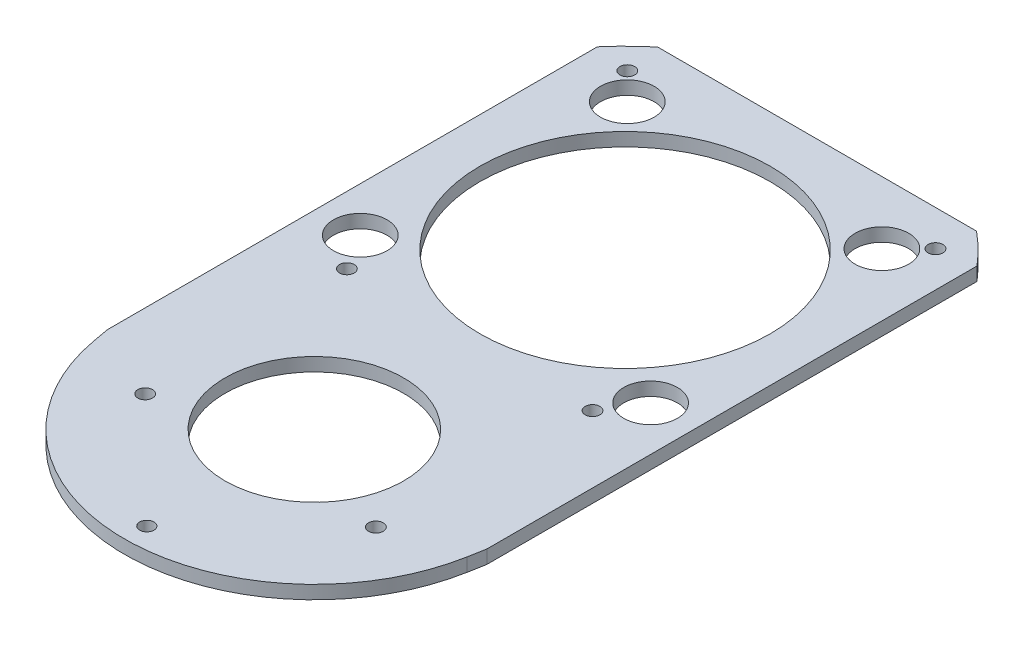
SolidWorks part; units mm, degrees
ref_plane "Front Plane" through (0, 0, 0) normal (0, 0, 1) x (1, 0, 0)
ref_plane "Top Plane" through (0, 0, 0) normal (0, 1, 0) x (1, 0, 0)
ref_plane "Right Plane" through (0, 0, 0) normal (1, 0, 0) x (0, 0, -1)
sketch "Sketch1" plane through (0, 0, 0) normal (0, 1, 0) x (1, 0, 0)
  line L0 (0, 0) -> (0, -69.5691) construction
  line L1 (0, 0) -> (0, -69.5691) construction
  line L2 (-42.5, -73.412) -> (-41.8107, -77.1925)
  line L3 (42.5, -73.412) -> (41.8107, -77.1925)
  line L4 (42.5, 36.2892) -> (42.5, -73.412)
  line L5 (-22.5, -47.0691) -> (22.5, -47.0691) construction
  line L6 (-35.6953, 43) -> (35.6953, 43)
  line L7 (-22.5, -47.0691) -> (-22.5, -92.0691) construction
  line L8 (-22.5, -92.0691) -> (22.5, -92.0691) construction
  line L9 (22.5, -47.0691) -> (22.5, -92.0691) construction
  line L10 (-22.5, -47.0691) -> (22.5, -92.0691) construction
  line L11 (-22.5, -92.0691) -> (22.5, -47.0691) construction
  line L12 (-42.5, 36.2892) -> (-42.5, -73.412)
  arc A0 (42.5, 36.2892) -> (35.6953, 43) centre (0, 0) ccw
  arc A1 (-41.8107, -77.1925) -> (41.8107, -77.1925) centre (0, -69.5691) ccw
  circle A2 centre (0, 0) radius 32.5
  circle A3 centre (0, -69.5691) radius 20
  arc A4 (-35.6953, 43) -> (-42.5, 36.2892) centre (0, 0) ccw
  point P1 (0, -34.7846)
  dimension "D1" = 65
  dimension "D2" = 40
  dimension "D7" = 85
  dimension "D3" = 69.5691
  dimension "D4" = 43
  dimension "D5" = 45
  dimension "D6" = 45
  dimension "D8" = 42.5
  dimension "D9" = 42.5
extrude "Boss-Extrude1" add sketch "Sketch1" along normal blind 3
sketch "Sketch4" plane through (0, 3, 0) normal (0, 1, 0) x (1, 0, 0)
  line L1 (-22.5, -47.0691) -> (22.5, -47.0691)
  line L2 (-22.5, -47.0691) -> (-22.5, -92.0691)
  line L3 (-22.5, -92.0691) -> (22.5, -92.0691)
  line L4 (22.5, -47.0691) -> (22.5, -92.0691)
  line L5 (-22.5, -47.0691) -> (22.5, -92.0691) construction
  line L6 (-22.5, -92.0691) -> (22.5, -47.0691) construction
  circle A0 centre (0, 0) radius 42.5
  point P3 (0, -69.5691)
  dimension "D1" = 45
  dimension "D2" = 45
sketch "Sketch5" plane through (0, 3, 0) normal (0, 1, 0) x (1, 0, 0)
  circle A0 centre (0, -107.0691) radius 1.6
  arc A1 (-41.8107, -77.1925) -> (41.8107, -77.1925) centre (0, -69.5691) ccw construction
  dimension "D2" = 3.2
  dimension "D1" = 37.5
extrude "Cut-Extrude1" cut sketch "Sketch5" against normal blind 10
sketch "Sketch6" plane through (0, 3, 0) normal (0, 1, 0) x (1, 0, 0)
  line L0 (35.6953, 43) -> (-35.6953, 43) construction
  line L1 (-42.5, 36.2892) -> (-42.5, -73.412) construction
  circle A0 centre (-34.5, 35) radius 1.65
  circle A1 centre (34.5, 35) radius 1.65
  circle A2 centre (27.5, -34.7846) radius 1.65
  circle A3 centre (25.8298, -81.6138) radius 1.65
  circle A4 centre (-25.8298, -81.6138) radius 1.65
  circle A5 centre (-27.5, -34.7846) radius 1.65
  dimension "D1" = 3.3
  dimension "D4" = 3.3
  dimension "D5" = 3.3
  dimension "D6" = 3.3
  dimension "D7" = 3.3
  dimension "D8" = 3.3
  dimension "D2" = 8
  dimension "D3" = 8
extrude "Cut-Extrude2" cut sketch "Sketch6" against normal blind 10
sketch "Sketch7" plane through (0, 3, 0) normal (0, 1, 0) x (1, 0, 0)
  line L0 (-37.5, -69.5691) -> (-37.5, 0)
  line L1 (37.5, -69.5691) -> (37.5, 0)
  arc A1 (37.5, 0) -> (-37.5, 0) centre (0, 0) ccw
  arc A2 (-37.5, -69.5691) -> (37.5, -69.5691) centre (0, -69.5691) ccw
  dimension "D2" = 75
  dimension "D3" = 75
sketch "Sketch8" plane through (0, 0, 0) normal (0, -1, 0) x (1, 0, 0)
  line L0 (35.6953, -43) -> (-35.6953, -43) construction
  line L1 (42.5, 73.412) -> (42.5, -36.2892) construction
  line L2 (0, 0) -> (0, -110.744) construction
  circle A0 centre (28.5, -29) radius 6
  circle A1 centre (32.5, 26.7846) radius 6
  circle A2 centre (27.5, 34.7846) radius 1.65 construction
  circle A3 centre (-32.5, 26.7846) radius 6
  circle A4 centre (-28.5, -29) radius 6
  dimension "D1" = 12
  dimension "D5" = 12
  dimension "D2" = 14
  dimension "D3" = 14
  dimension "D4" = 10
  dimension "D6" = 8
extrude "Cut-Extrude3" cut sketch "Sketch8" against normal blind 10
equation "\"D3@LPattern1\"=2*18.4"
equation "\"D4@LPattern1\"=2*18.4"
equation "\"D4@Sketch1\"=\"D1@Sketch1\"/2+10.5"
equation "\"D8@Sketch1\"=85/2"
equation "\"D9@Sketch1\"=\"D8@Sketch1\""
equation "\"D2@Sketch7\"=\"D1@Sketch7\"-10"
equation "\"D3@Sketch7\"=42.5*2-10"
equation "\"D5@Sketch6\"=\"D4@Sketch6\""
equation "\"D6@Sketch6\"=\"D1@Sketch6\""
equation "\"D7@Sketch6\"=\"D1@Sketch6\""
equation "\"D8@Sketch6\"=\"D1@Sketch6\""
equation "\"D3@Sketch8\"=\"D2@Sketch8\""
